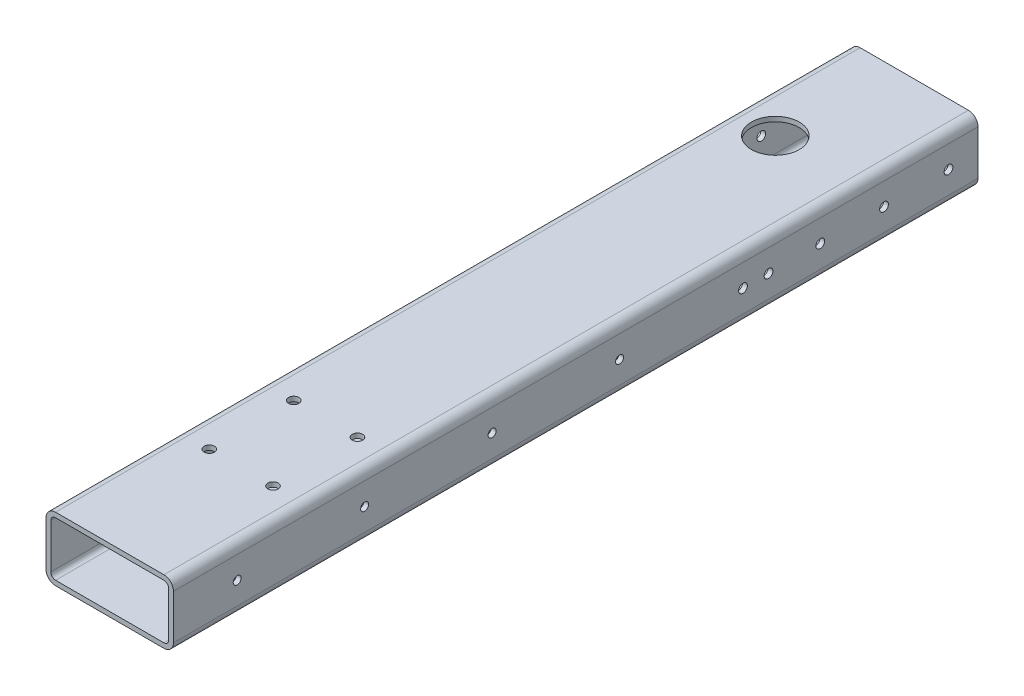
SolidWorks part; units mm, degrees
material "1.0038 (S235JRG2)"
ref_plane "Ebene vorne" through (0, 0, 0) normal (0, 0, 1) x (1, 0, 0)
ref_plane "Ebene oben" through (0, 0, 0) normal (0, 1, 0) x (1, 0, 0)
ref_plane "Ebene rechts" through (0, 0, 0) normal (1, 0, 0) x (0, 0, -1)
sketch "Skizze1" plane through (0, 0, 0) normal (0, 0, 1) x (1, 0, 0)
  line L0 (0, 0) -> (0, 67.8952) construction
  line L1 (-34, 20) -> (34, 20)
  line L2 (0, 0) -> (65.406, 0) construction
  line L3 (40, 14) -> (40, -14)
  line L4 (-40, 14) -> (-40, -14)
  line L5 (-34, -20) -> (34, -20)
  line L6 (-37, 14) -> (-37, -14)
  line L7 (-34, -17) -> (34, -17)
  line L8 (37, 14) -> (37, -14)
  line L9 (-34, 17) -> (34, 17)
  arc A0 (34, 20) -> (40, 14) centre (34, 14) cw
  arc A1 (-34, 20) -> (-40, 14) centre (-34, 14) ccw
  arc A2 (-34, -20) -> (-40, -14) centre (-34, -14) cw
  arc A3 (34, -20) -> (40, -14) centre (34, -14) ccw
  arc A4 (-34, -17) -> (-37, -14) centre (-34, -14) cw
  arc A5 (34, -17) -> (37, -14) centre (34, -14) ccw
  arc A6 (34, 17) -> (37, 14) centre (34, 14) cw
  arc A7 (-34, 17) -> (-37, 14) centre (-34, 14) ccw
  point P12 (40, 0)
  point P13 (0, 20)
  point P19 (-40, 0)
  dimension "D1" = 6
  dimension "D3" = 80
  dimension "D4" = 40
  dimension "D2" = 3
extrude "Aufsatz-Linear austragen1" add sketch "Skizze1" along normal blind 505
sketch "Skizze2" plane through (0, 20, 0) normal (0, 1, 0) x (1, 0, 0)
  line L0 (0, 0) -> (0, -537.8853) construction
  line L1 (20, -369.5) -> (20, -422.5) construction
  line L3 (34, -505) -> (-34, -505) construction
  circle A0 centre (20, -369.5) radius 3.25
  circle A1 centre (20, -422.5) radius 3.25
  circle A2 centre (-20, -422.5) radius 3.25
  circle A3 centre (-20, -369.5) radius 3.25
  dimension "D1" = 6.5
  dimension "D2" = 53
  dimension "D3" = 40
  dimension "D4" = 82.5
extrude "Schnitt-Linear austragen1" cut sketch "Skizze2" against normal blind 60
sketch "Skizze3" plane through (40, 0, 0) normal (1, 0, 0) x (0, 0, -1)
  line L0 (0, 0) -> (-186.4604, 0) construction
  line L1 (0, -14) -> (0, 14) construction
  circle A0 centre (-18.5, 0) radius 2.75
  circle A1 centre (-59, 0) radius 2.75
  circle A2 centre (-99, 0) radius 2.75
  circle A3 centre (-131.5, 0) radius 2.75
  circle A4 centre (-147.5, 0) radius 2.75
  dimension "D1" = 5.5
  dimension "D4" = 99
  dimension "D5" = 16
  dimension "D6" = 131.5
  dimension "D2" = 18.5
  dimension "D3" = 40.5
extrude "Schnitt-Linear austragen2" cut sketch "Skizze3" against normal blind 100
sketch "Skizze4" plane through (0, -20, 0) normal (0, -1, 0) x (1, 0, 0)
  line L0 (-34, 0) -> (34, 0) construction
  line L1 (-40, 505) -> (-40, 0) construction
  circle A0 centre (-12.7, 74.5) radius 15
  dimension "D1" = 74.5
  dimension "D2" = 30
  dimension "D3" = 27.3
extrude "Schnitt-Linear austragen3" cut sketch "Skizze4" against normal blind 100
sketch "Skizze5" plane through (-40, 0, 0) normal (-1, 0, 0) x (0, 0, 1)
  line L0 (0, 0) -> (527.5076, 0) construction
  line L1 (505, 14) -> (505, -14) construction
  circle A0 centre (465, 0) radius 2.5
  circle A1 centre (385, 0) radius 2.5
  circle A2 centre (305, 0) radius 2.5
  circle A3 centre (225, 0) radius 2.5
  dimension "D2" = 80
  dimension "D3" = 80
  dimension "D4" = 80
  dimension "D5" = 5
  dimension "D1" = 40
extrude "Schnitt-Linear austragen4" cut sketch "Skizze5" against normal blind 100
sketch "Skizze6" plane through (0, -20, 0) normal (0, -1, 0) x (1, 0, 0)
  line L0 (-12.7, 74.5) -> (-68.2797, 74.5) construction
  line L1 (-12.7, 74.5) -> (-12.7, 18.8442) construction
  line L2 (-12.7, 74.5) -> (-29.3524, 57.8476) construction
  line L3 (-29.3524, 57.8476) -> (-12.7, 41.1953) construction
  line L4 (-12.7, 41.1953) -> (20.6047, 74.5) construction
  line L5 (20.6047, 74.5) -> (-12.7, 107.8047) construction
  line L6 (-12.7, 107.8047) -> (-46.0047, 74.5) construction
  line L7 (-46.0047, 74.5) -> (-29.3524, 57.8476) construction
  line L8 (-12.7, 74.5) -> (3.9524, 91.1524) construction
  circle A0 centre (-12.7, 41.1953) radius 3
  circle A1 centre (20.6047, 74.5) radius 3
  circle A2 centre (-12.7, 107.8047) radius 3
  circle A3 centre (-46.0047, 74.5) radius 3
  dimension "D4" = 6
  dimension "D1" = 47.1
  dimension "D2" = 47.1
  dimension "D3" = 45
extrude "Schnitt-Linear austragen5" cut sketch "Skizze6" against normal blind 10
sketch "Skizze7" plane through (0, -20, 0) normal (0, -1, 0) x (1, 0, 0)
  circle A0 centre (-12.7, 74.5) radius 20
  dimension "D1" = 40
extrude "Schnitt-Linear austragen6" cut sketch "Skizze7" against normal blind 5
